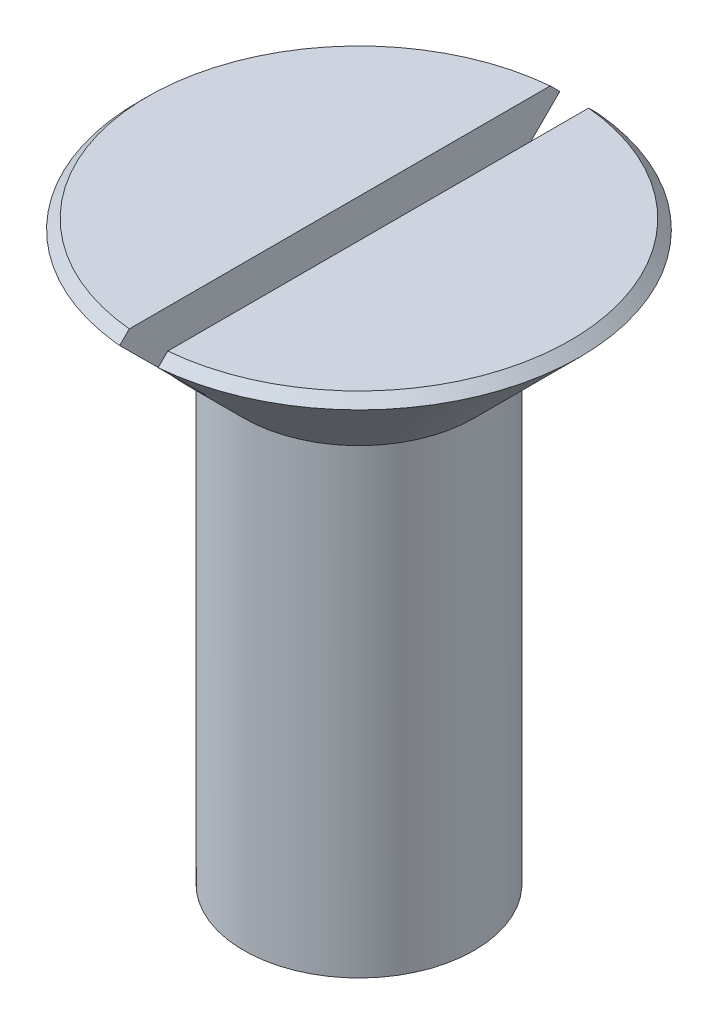
SolidWorks part; units mm, degrees
material "Plain Carbon Steel"
ref_plane "Front Plane" through (0, 0, 0) normal (0, 0, 1) x (1, 0, 0)
ref_plane "Top Plane" through (0, 0, 0) normal (0, 1, 0) x (1, 0, 0)
ref_plane "Right Plane" through (0, 0, 0) normal (1, 0, 0) x (0, 0, -1)
sketch "Sketch2" plane through (0, 0, 0) normal (0, 0, 1) x (1, 0, 0)
  line L0 (0, 0) -> (0, 30)
  line L1 (0, 30) -> (12, 30)
  line L2 (12, 30) -> (6, 24)
  line L3 (6, 24) -> (6, 0)
  line L4 (6, 0) -> (0, 0)
  dimension "D1" = 6
  dimension "D2" = 30
  dimension "D3" = 12
  dimension "D4" = 6
revolve "Revolve1" add sketch "Sketch2" angle 360 about L0
cosmetic thread "Cosmetic Thread1" parameters "D1"=22, "D2"=10.072
sketch "Sketch3" plane through (0, 0, 0) normal (0, 0, 1) x (1, 0, 0)
  line L0 (-1, 30) -> (1, 30)
  line L1 (12, 30) -> (-12, 30) construction
  line L2 (1, 30) -> (1, 27)
  line L3 (1, 27) -> (-1, 27)
  line L4 (-1, 27) -> (-1, 30)
  point P5 (0, 30)
  point P6 (0, 0)
  dimension "D1" = 2
  dimension "D2" = 3
extrude "Cut-Extrude1" cut sketch "Sketch3" against normal through all both and the other way through all
chamfer "Chamfer1" distance 1 angle 45 2 edges at (12, 30, 0) (-12, 30, 0)
